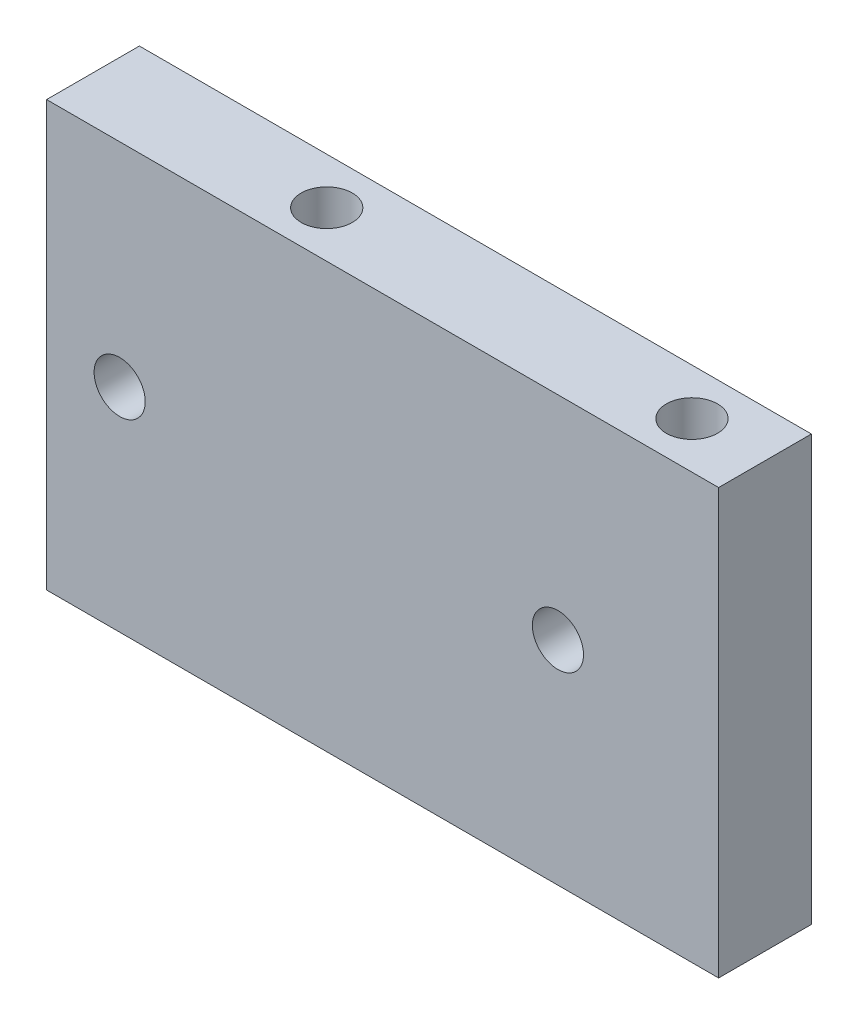
SolidWorks part; units mm, degrees
material "6061 Alloy"
ref_plane "Front Plane" through (0, 0, 0) normal (0, 0, 1) x (1, 0, 0)
ref_plane "Top Plane" through (0, 0, 0) normal (0, 1, 0) x (1, 0, 0)
ref_plane "Right Plane" through (0, 0, 0) normal (1, 0, 0) x (0, 0, -1)
sketch "Sketch1" plane through (0, 0, 0) normal (0, 0, 1) x (1, 0, 0)
  line L1 (-23, 14.5375) -> (23, 14.5375)
  line L2 (-23, 14.5375) -> (-23, -14.5375)
  line L3 (-23, -14.5375) -> (23, -14.5375)
  line L4 (23, 14.5375) -> (23, -14.5375)
  line L5 (0, -14.5375) -> (0, 14.5375) construction
  line L6 (-23, 0) -> (23, 0) construction
  point P0 (0, 0)
  dimension "D1" = 29.075
  dimension "D2" = 46
extrude "1/4" add sketch "Sketch1" along normal blind 6.35
sketch "Sketch2" plane through (0, 0, 0) normal (0, 0, 1) x (1, 0, 0)
  line L0 (0, 0) -> (-18, 0) construction
  line L1 (0, 0) -> (0, 8.9877) construction
  line L2 (-23, 14.5375) -> (-23, -14.5375) construction
  circle A0 centre (-18, 0) radius 1.75
  circle A2 centre (12, 0) radius 1.75
  dimension "D2" = 3.5
  dimension "D1" = 5
  dimension "D3" = 2
extrude "M4_DRILL" cut sketch "Sketch2" along normal up to surface (6.35 mm away) up to face at (0, 0, 6.35)
sketch "Sketch3" plane through (0, -14.5375, 0) normal (0, -1, 0) x (1, 0, 0)
  line L0 (-23, 3.175) -> (-7, 3.175) construction
  line L1 (-23, 6.35) -> (-23, 0) construction
  circle A0 centre (-7, 3.175) radius 1.75
  circle A1 centre (18, 3.175) radius 1.75
  dimension "D1" = 3.5
  dimension "D2" = 16
  dimension "D3" = 2
extrude "M4_DRILL2" cut sketch "Sketch3" against normal blind 8
sketch "Sketch4" plane through (0, 14.5375, 0) normal (0, 1, 0) x (1, 0, 0)
  circle A0 centre (18, -3.175) radius 1.75 construction
  circle A1 centre (-7, -3.175) radius 1.75 construction
  circle A2 centre (18, -3.175) radius 1.75
  circle A3 centre (-7, -3.175) radius 1.75
extrude "M4_DRILL3" cut sketch "Sketch4" against normal blind 8
